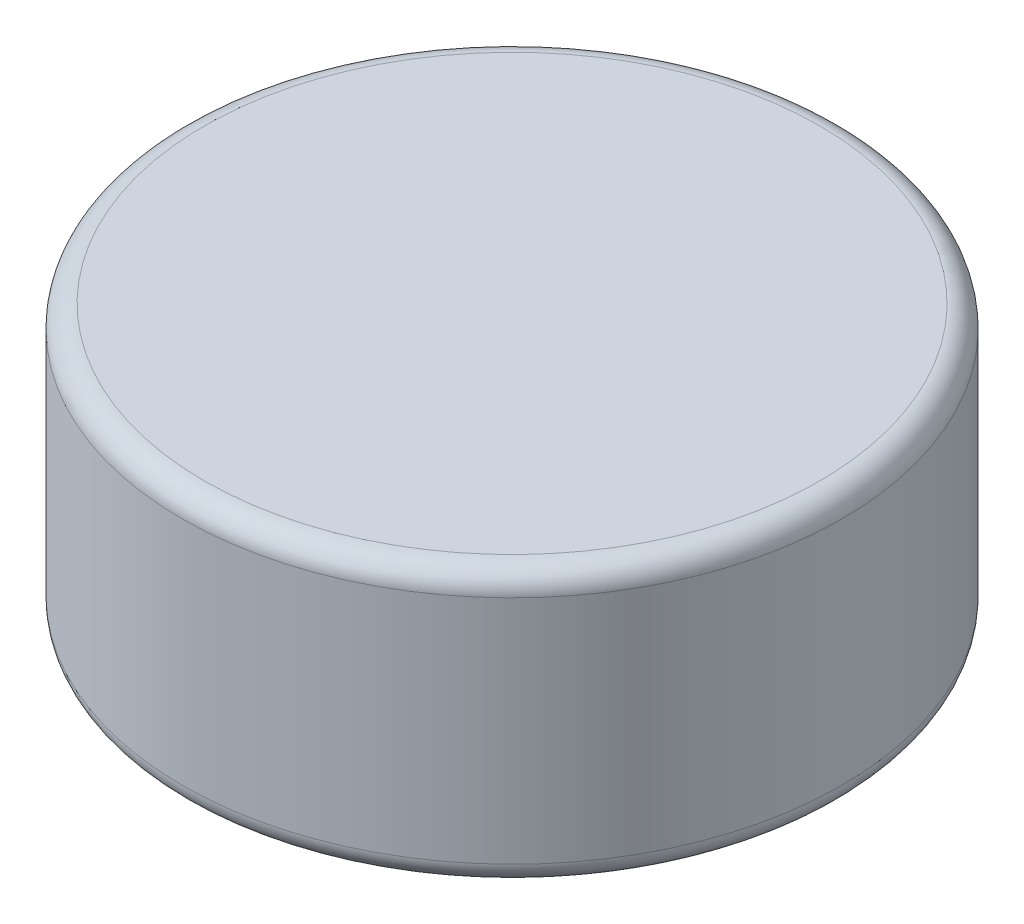
SolidWorks part; units mm, degrees
ref_plane "Front Plane" through (0, 0, 0) normal (0, 0, 1) x (1, 0, 0)
ref_plane "Top Plane" through (0, 0, 0) normal (0, 1, 0) x (1, 0, 0)
ref_plane "Right Plane" through (0, 0, 0) normal (1, 0, 0) x (0, 0, -1)
sketch "Sketch1" plane through (0, 0, 0) normal (0, 1, 0) x (1, 0, 0)
  circle A0 centre (0, 0) radius 3
  dimension "D1" = 6
extrude "Boss-Extrude1" add sketch "Sketch1" along normal blind 2.5
fillet "Fillet1" radius 0.2 2 edges at (0, 0, 3) (0, 2.5, 3)
